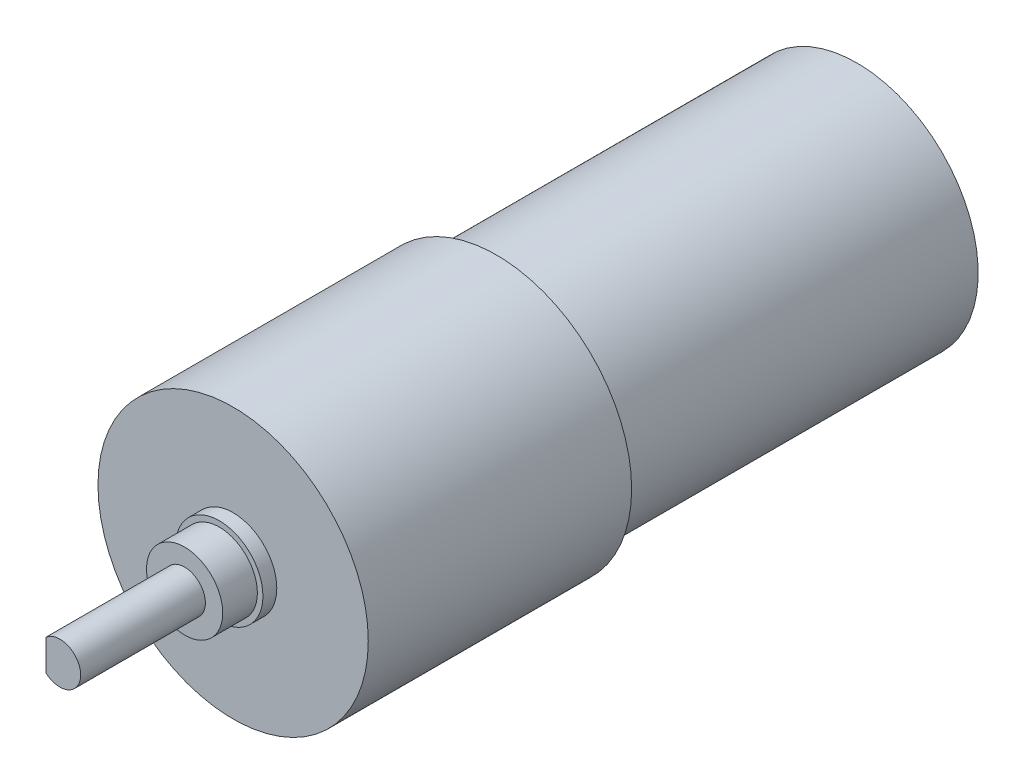
SolidWorks part; units mm, degrees
ref_plane "Front Plane" through (0, 0, 0) normal (0, 0, 1) x (1, 0, 0)
ref_plane "Top Plane" through (0, 0, 0) normal (0, 1, 0) x (1, 0, 0)
ref_plane "Right Plane" through (0, 0, 0) normal (1, 0, 0) x (0, 0, -1)
sketch "Sketch1" plane through (0, 0, 0) normal (0, 0, 1) x (1, 0, 0)
  circle A0 centre (0, 0) radius 8.75
  dimension "D1" = 17.5
extrude "Boss-Extrude1" add sketch "Sketch1" along normal blind 26
sketch "Sketch2" plane through (0, 0, 26) normal (0, 0, 1) x (1, 0, 0)
  circle A0 centre (0, 0) radius 9.75
  dimension "D1" = 19.5
extrude "Boss-Extrude2" add sketch "Sketch2" along normal blind 19
sketch "Sketch3" plane through (0, 0, 45) normal (0, 0, 1) x (1, 0, 0)
  circle A0 centre (0, 0) radius 3.15
  dimension "D1" = 6.3
extrude "Boss-Extrude3" add sketch "Sketch3" along normal blind 1
sketch "Sketch4" plane through (0, 0, 46) normal (0, 0, 1) x (1, 0, 0)
  circle A0 centre (0, 0) radius 2.75
  dimension "D1" = 5.5
extrude "Boss-Extrude4" add sketch "Sketch4" along normal blind 2.5
sketch "Sketch5" plane through (0, 0, 48.5) normal (0, 0, 1) x (1, 0, 0)
  line L0 (-1, 1.118) -> (-1, -1.118)
  arc A0 (-1, -1.118) -> (-1, 1.118) centre (0, 0) ccw
  dimension "D1" = 1
  dimension "D2" = 3
extrude "Boss-Extrude5" add sketch "Sketch5" along normal blind 9
